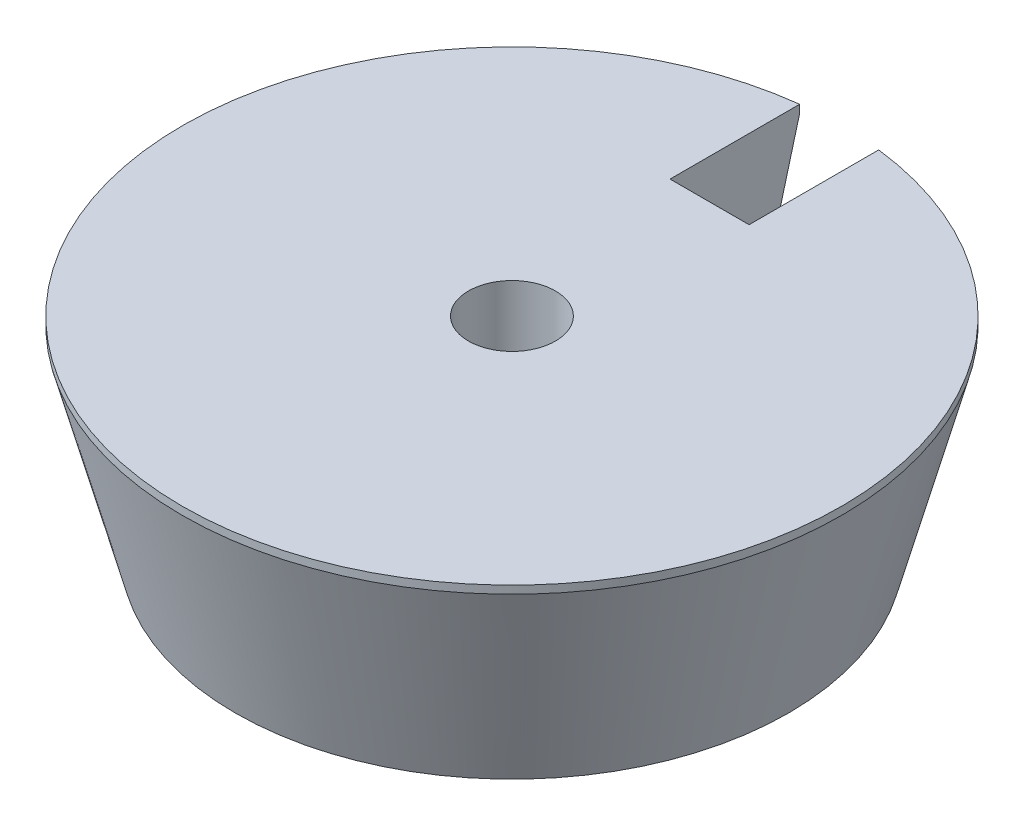
SolidWorks part; units mm, degrees
ref_plane "Front Plane" through (0, 0, 0) normal (0, 0, 1) x (1, 0, 0)
ref_plane "Top Plane" through (0, 0, 0) normal (0, 1, 0) x (1, 0, 0)
ref_plane "Right Plane" through (0, 0, 0) normal (1, 0, 0) x (0, 0, -1)
sketch "Sketch1" plane through (0, 0, 0) normal (0, 1, 0) x (1, 0, 0)
  circle A0 centre (0, 0) radius 35
  dimension "D1" = 35
extrude "Extrude1" add sketch "Sketch1" along normal blind 25 draft 15 draft outward yes
sketch "Sketch2" plane through (0, 0, 0) normal (0, -1, 0) x (1, 0, 0)
  circle A0 centre (0, 0) radius 8
  dimension "D1" = 16
extrude "Extrude2" add sketch "Sketch2" along normal blind 12
sketch "Sketch3" plane through (0, 25, 0) normal (0, 1, 0) x (1, 0, 0)
  line L1 (-5, 55) -> (5, 55)
  line L2 (-5, 55) -> (-5, 25)
  line L3 (-5, 25) -> (5, 25)
  line L4 (5, 55) -> (5, 25)
  dimension "D1" = 10
  dimension "D2" = 5
  dimension "D3" = 25
  dimension "D4" = 30
extrude "Cut-Extrude1" cut sketch "Sketch3" against normal through all
sketch "Sketch5" plane through (0, 25, 0) normal (0, 1, 0) x (1, 0, 0)
  circle A0 centre (0, 0) radius 16 construction
  text T0 "BIO ENGINEERING"
  line M2 (-5, 25) -> (-5, 41.3979)
  arc M3 (-5, 41.3979) -> (5, 41.3979) centre (0, 0) ccw
  line M4 (5, 41.3979) -> (5, 25)
  line M5 (5, 25) -> (-5, 25)
  dimension "D1" = 32
extrude "Extrude4" add sketch "Sketch5" along normal blind 1 contours M2 M3 M4 M5
hole_wizard "Ø11.0 (11) Diameter Hole1" positions "Sketch7" profile "Sketch8" hole size "Ø11.0" standard "ANSI Metric" end condition through all
sketch "Sketch7" plane through (0, 26, 0) normal (0, 1, 0) x (1, 0, 0)
  point P0 (0, 0)
sketch "Sketch8" plane through (0, 26, 0) normal (1, 0, 0) x (0, 0, 1)
  line L0 (0, 0) -> (0, 38)
  line L1 (0, 38) -> (5.5, 38)
  line L2 (5.5, 38) -> (5.5, 0)
  line L5 (5.5, 0) -> (0, 0)
  line L11 (0, -6.35) -> (0, 107.95) construction
  dimension "Thru Hole Dia." = 11
  dimension "Thru Hole Depth" = 38
sketch "Sketch9" plane through (0, 26, 0) normal (0, 1, 0) x (1, 0, 0)
  circle A0 centre (0, 0) radius 20
  circle A1 centre (0, 0) radius 15
  dimension "D1" = 40
  dimension "D2" = 30
extrude "groove" [suppressed] cut sketch "Sketch9" against normal blind 1
